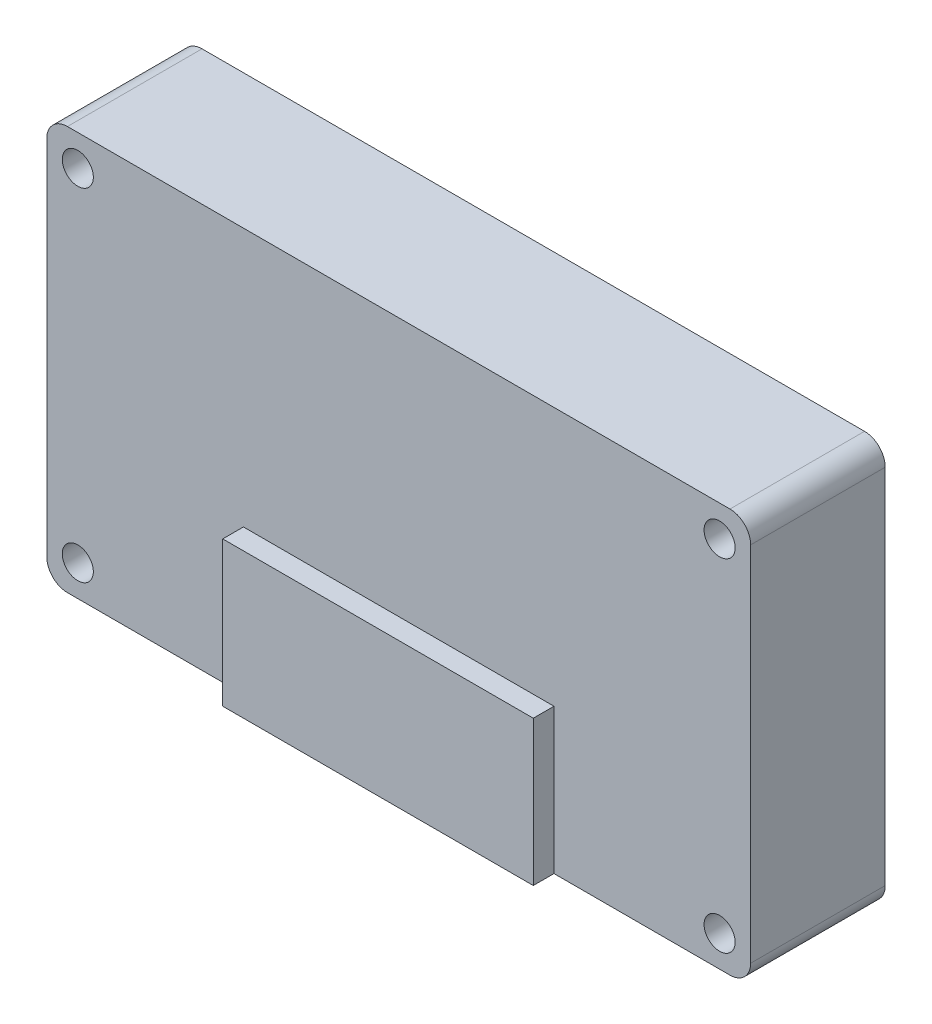
SolidWorks part; units mm, degrees
ref_plane "Alzado" through (0, 0, 0) normal (0, 0, 1) x (1, 0, 0)
ref_plane "Planta" through (0, 0, 0) normal (0, 1, 0) x (1, 0, 0)
ref_plane "Vista lateral" through (0, 0, 0) normal (1, 0, 0) x (0, 0, -1)
sketch "Croquis1" plane through (0, 0, 0) normal (0, 0, 1) x (1, 0, 0)
  line L0 (34, 0) -> (34, 12.7721) construction
  line L1 (0, 0) -> (68, 0)
  line L2 (0, 0) -> (0, 39)
  line L3 (0, 39) -> (68, 39)
  line L4 (68, 0) -> (68, 39)
  circle A0 centre (3, 36) radius 1.5
  circle A1 centre (3, 3) radius 1.5
  circle A2 centre (65, 36) radius 1.5
  circle A3 centre (65, 3) radius 1.5
  dimension "D3" = 3
  dimension "D7" = 3
  dimension "D1" = 68
  dimension "D2" = 39
  dimension "D4" = 3
  dimension "D5" = 3
  dimension "D6" = 3
extrude "Saliente-Extruir1" add sketch "Croquis1" along normal blind 13
fillet "Redondeo1" radius 2 4 edges at (0, 0, 6.5) (68, 0, 6.5) (68, 39, 6.5) (0, 39, 6.5)
sketch "Croquis2" plane through (0, 0, 13) normal (0, 0, 1) x (1, 0, 0)
  line L0 (0, 37) -> (0, 2) construction
  line L1 (19, 14) -> (49, 14)
  line L2 (19, 14) -> (19, 0)
  line L3 (19, 0) -> (49, 0)
  line L4 (49, 14) -> (49, 0)
  line L5 (2, 0) -> (66, 0) construction
  dimension "D1" = 19
  dimension "D2" = 14
  dimension "D3" = 30
extrude "Saliente-Extruir2" add sketch "Croquis2" along normal blind 2
